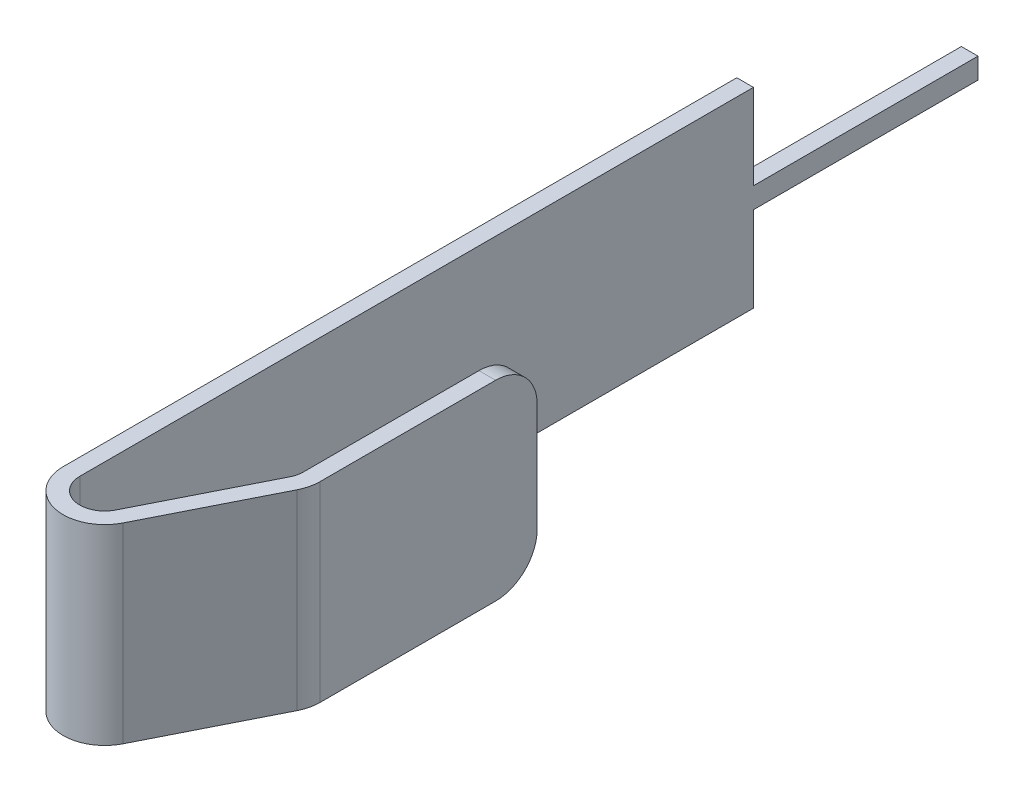
SolidWorks part; units mm, degrees
ref_plane "Front Plane" through (0, 0, 0) normal (0, 0, 1) x (1, 0, 0)
ref_plane "Top Plane" through (0, 0, 0) normal (0, 1, 0) x (1, 0, 0)
ref_plane "Right Plane" through (0, 0, 0) normal (1, 0, 0) x (0, 0, -1)
sketch "Sketch1" plane through (0, 0, 0) normal (0, 1, 0) x (1, 0, 0)
  line L0 (0, 0) -> (0, -20.574)
  line L1 (2.4044, -21.1451) -> (4.1824, -17.6132)
  line L2 (4.318, -17.0421) -> (4.318, -10.414)
  line L3 (0, 0) -> (0, 6.858)
  arc A0 (4.318, -17.0421) -> (4.1824, -17.6132) centre (3.048, -17.0421) cw
  arc A1 (2.4044, -21.1451) -> (0, -20.574) centre (1.27, -20.574) cw
  dimension "D1" = 1.27
  dimension "D2" = 11.43
  dimension "D4" = 21.844
  dimension "D3" = 4.318
  dimension "D5" = 3.5319
  dimension "D6" = 6.858
extrude "Extrude-Thin1" add sketch "Sketch1" along normal mid plane 5.842 thin thin type one direction wall 0.508
fillet "Fillet1" radius 1.27 2 edges at (4.064, -2.921, 10.414) (4.064, 2.921, 10.414)
sketch "Sketch2" plane through (0, 0, 0) normal (-1, 0, 0) x (0, 0, 1)
  line L0 (-6.858, 0) -> (0, 0) construction
  line L1 (-6.858, 2.921) -> (0, 2.921)
  line L2 (-6.858, 2.921) -> (-6.858, 0.3175)
  line L3 (-6.858, 0.3175) -> (0, 0.3175)
  line L4 (0, 2.921) -> (0, 0.3175)
  line L5 (-6.858, 2.921) -> (-6.858, -2.921) construction
  line L6 (-6.858, -2.921) -> (0, -2.921)
  line L7 (-6.858, -2.921) -> (-6.858, -0.3175)
  line L8 (-6.858, -0.3175) -> (0, -0.3175)
  line L9 (0, -2.921) -> (0, -0.3175)
  dimension "D1" = 0.635
extrude "Cut-Extrude1" cut sketch "Sketch2" against normal through all
